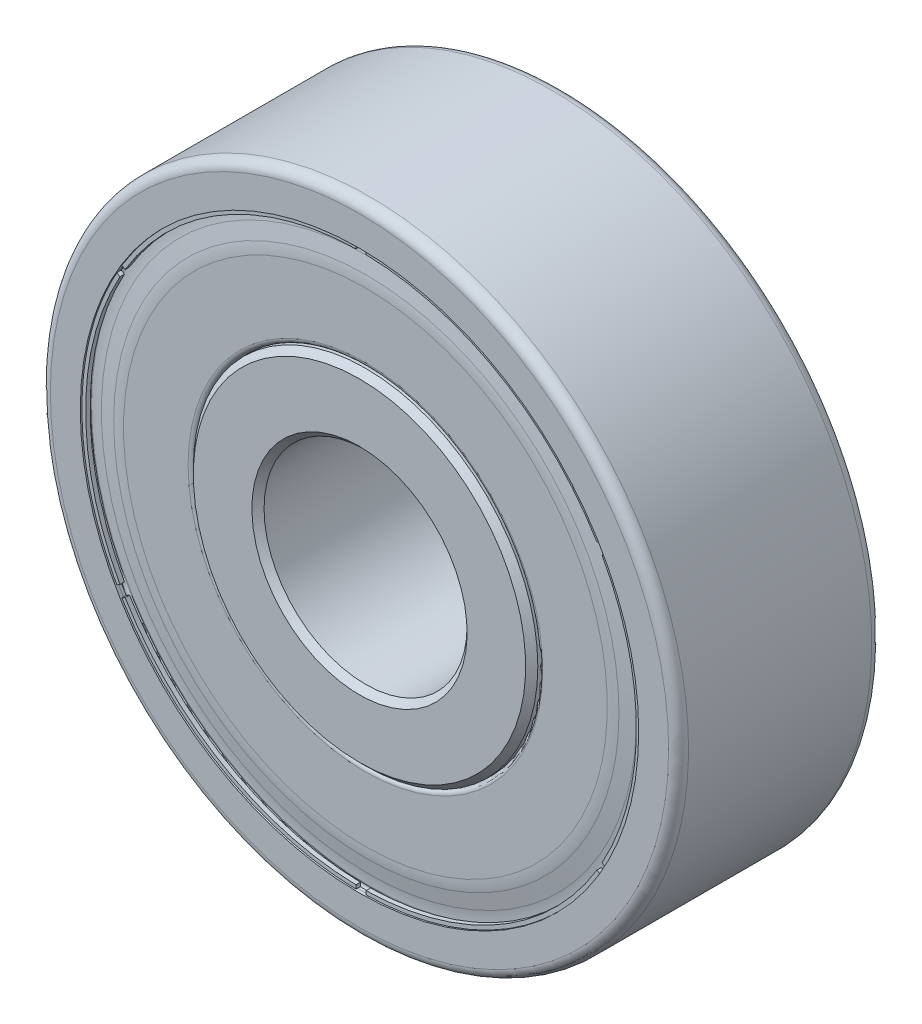
SolidWorks part; units mm, degrees
ref_plane "Front Plane" through (0, 0, 0) normal (0, 0, 1) x (1, 0, 0)
ref_plane "Top Plane" through (0, 0, 0) normal (0, 1, 0) x (1, 0, 0)
ref_plane "Right Plane" through (0, 0, 0) normal (1, 0, 0) x (0, 0, -1)
sketch "Sketch1" plane through (0, 0, 0) normal (0, 0, 1) x (1, 0, 0)
  line L0 (-11, 0) -> (-3.5, 0) construction
  line L1 (-3.5, 0) -> (3.5, 0) construction
  line L2 (3.5, 0) -> (11, 0) construction
  line L3 (0, 11) -> (0, 3.5) construction
  line L4 (0, 3.5) -> (0, 0) construction
  circle A0 centre (0, 0) radius 3.5 construction
  circle A1 centre (0, 0) radius 11 construction
  point P0 (0, 0)
  point P9 (0, 11)
  point P10 (0, 3.5)
  dimension "For Housing ID" = 22
  dimension "For Shaft Diameter" = 7
  dimension "OD" = 22
  dimension "ID" = 7
sketch "Sketch2" plane through (0, 0, 0) normal (1, 0, 0) x (0, 0, -1)
  line L1 (-3.5, -11) -> (3.5, -11) construction
  line L2 (-3.5, -11) -> (-3.5, 11) construction
  line L3 (-3.5, 11) -> (3.5, 11) construction
  line L4 (3.5, -11) -> (3.5, 11) construction
  line L5 (0, 11) -> (0, -11) construction
  line L6 (-3.5, 0) -> (3.5, 0) construction
  dimension "Width" = 7
sketch "Sketch3" plane through (0, 0, 0) normal (1, 0, 0) x (0, 0, -1)
  line L0 (-3.1562, 11) -> (3.5, 11) construction
  line L1 (-3.5, 3.5) -> (3.5, 3.5)
  line L2 (-3.5, -11) -> (-3.5, 11) construction
  line L3 (3.5, -11) -> (3.5, 11) construction
  line L4 (-3.5, 3.5) -> (-3.5, 5.9375)
  line L5 (-3.5, 5.9375) -> (3.5, 5.9375) construction
  line L6 (3.5, 5.9375) -> (3.5, 3.5)
  line L7 (-3.5, 11) -> (-3.5, 9.625) construction
  line L8 (-3.5, 9.625) -> (3.5, 9.625) construction
  line L9 (3.5, 9.625) -> (3.5, 11) construction
  line L10 (0, 9.625) -> (0, 5.9375) construction
  line L11 (0, 9.9687) -> (0, 9.625) construction
  line L12 (0, 9.9687) -> (0, 10.3125) construction
  line L13 (0, 11) -> (0, 3.5) construction
  line L14 (0, 10.3125) -> (0, 10.6562) construction
  line L15 (0, 10.6562) -> (0, 11) construction
  line L21 (3.5, 9.625) -> (3.395, 9.625)
  line L22 (-3.5, 9.625) -> (-3.395, 9.625)
  line L23 (-3.0477, 9.6554) -> (-2.9453, 9.075)
  line L24 (-2.9453, 9.075) -> (-1.7639, 9.075)
  line L25 (1.7639, 9.075) -> (2.9453, 9.075)
  line L26 (2.9453, 9.075) -> (3.0477, 9.6554)
  line L27 (-3.5, 5.9375) -> (-1.1772, 5.9375)
  line L28 (3.5, 5.9375) -> (1.1772, 5.9375)
  line L29 (-3.1562, 11) -> (3.1562, 11)
  line L31 (3.5, 10.6563) -> (3.5, 9.625)
  line L33 (-3.5, 10.6563) -> (-3.5, 9.625)
  circle A0 centre (0, 7.7812) radius 2.1875 construction
  arc A3 (-3.395, 9.625) -> (-3.0477, 9.6554) centre (-3.22, 9.625) cw
  arc A4 (3.0477, 9.6554) -> (3.395, 9.625) centre (3.22, 9.625) cw
  arc A5 (-1.7639, 9.075) -> (1.7639, 9.075) centre (0, 7.7812) cw
  arc A8 (-1.1772, 5.9375) -> (1.1772, 5.9375) centre (0, 7.7812) ccw
  arc A9 (-3.1562, 11) -> (-3.5, 10.6563) centre (-3.1562, 10.6562) ccw
  arc A10 (3.5, 10.6563) -> (3.1562, 11) centre (3.1562, 10.6562) ccw
  dimension "D1" = 4.375
  dimension "D5" = 0.175
  dimension "REF" = 7.5
  dimension "D2" = 1.375
  dimension "D3" = 0.105
  dimension "D4" = 10
  dimension "D6" = 0.55
revolve "Revolve1" add sketch "Sketch3" angle 360 about L6
sketch "Sketch7" plane through (0, 0, 0) normal (0, 0, 1) x (1, 0, 0)
  line L0 (0, 11) -> (0, 0) construction
  line L1 (0, 5.5937) -> (0, 9.9687) construction
  line L2 (-2.0993, 7.1663) -> (0, 0) construction
  line L3 (0, 0) -> (2.0993, 7.1663) construction
  circle A0 centre (0, 7.7812) radius 2.1875 construction
  point P8 (0, 5.5937)
  dimension "Bearing Spacing" = 32.655
chamfer "Chamfer1" distance 0.21 angle 45 4 edges at (0, -3.5, -3.5) (0, -5.9375, -3.5) (0, -3.5, 3.5) (0, -5.9375, 3.5)
sketch "Sketch4" plane through (0, 0, 0) normal (1, 0, 0) x (0, 0, -1)
  line L0 (-3.395, 9.625) -> (-3.4475, 9.625)
  line L1 (-3.4475, 9.625) -> (-3.4475, 9.493)
  line L2 (-2.9453, 9.075) -> (-3.0477, 9.6554) construction
  line L3 (-3.4475, 9.625) -> (-3.5, 9.625) construction
  line L4 (-3.045, 9.625) -> (-3.045, 9.405)
  line L19 (-3.145, 9.405) -> (-3.045, 9.405) construction
  line L23 (-3.195, 8.525) -> (-3.195, 6.0375) construction
  line L25 (-3.195, 6.0375) -> (-2.1283, 6.0375) construction
  line L26 (-2.1283, 6.0375) -> (-2.1283, 5.9375)
  line L28 (-2.1283, 5.9375) -> (-3.295, 5.9375) construction
  line L29 (-3.295, 5.9375) -> (-3.295, 8.525) construction
  line L30 (-3.045, 9.405) -> (-3.195, 8.525)
  line L31 (-3.145, 9.405) -> (-3.145, 9.625)
  line L33 (-3.5, 5.9375) -> (-1.1772, 5.9375) construction
  line L35 (-3.4475, 9.493) -> (-3.295, 9.493)
  line L36 (-3.295, 9.493) -> (-3.295, 9.625)
  line L37 (-3.195, 7.2812) -> (-3.295, 7.2813) construction
  line L38 (-3.145, 9.405) -> (-3.295, 8.525)
  line L39 (-3.295, 9.493) -> (-3.295, 8.525) construction
  line L41 (-3.12, 5.9375) -> (-2.1283, 5.9375)
  line L42 (-3.12, 6.0375) -> (-2.1283, 6.0375)
  line L43 (-3.195, 6.1125) -> (-3.195, 8.525)
  line L44 (-3.295, 8.525) -> (-3.295, 6.1125)
  arc A0 (-3.045, 9.625) -> (-3.395, 9.625) centre (-3.22, 9.625) ccw
  arc A8 (-3.0477, 9.6554) -> (-3.395, 9.625) centre (-3.22, 9.625) ccw construction
  arc A9 (-3.145, 9.625) -> (-3.295, 9.625) centre (-3.22, 9.625) ccw
  arc A10 (-3.295, 6.1125) -> (-3.12, 5.9375) centre (-3.12, 6.1125) ccw
  arc A11 (-3.195, 6.1125) -> (-3.12, 6.0375) centre (-3.12, 6.1125) ccw
  point P24 (-3.0035, 9.405)
  dimension "D4" = 0.35
  dimension "D1" = 0.132
  dimension "D2" = 0.1
  dimension "D5" = 1.1667
  dimension "D6" = 0.22
  dimension "D3" = 0.88
revolve "Revolve2" add sketch "Sketch4" angle 360 about L6
fillet "Fillet1" radius 2.2 2 edges at (0, -8.525, 3.295) (0, -9.405, 3.145)
sketch "Sketch5" plane through (0, 0, 0) normal (1, 0, 0) x (0, 0, -1)
  line L0 (0, 9.9687) -> (0, 5.5937)
  circle A0 centre (0, 7.7812) radius 2.1875 construction
  arc A1 (0, 5.5937) -> (0, 9.9687) centre (0, 7.7812) ccw
revolve "Revolve3" add sketch "Sketch5" angle 360 about L0
pattern_circular "CirPattern1" count 6 over 360 about axis through (0, 0, 0) along (0, 0, 1) of bodies 107
sketch "Sketch6" plane through (0, 0, 3.4475) normal (0, 0, 1) x (1, 0, 0)
  line L0 (0, 9.625) -> (0, 0) construction
  line L1 (-0.175, 9.6234) -> (-0.175, 9.4914)
  line L2 (0.175, 9.6234) -> (0.175, 9.4914)
  line L3 (-0.175, 9.5574) -> (0.175, 9.5574) construction
  arc A0 (0.175, 9.4914) -> (-0.175, 9.4914) centre (0, 0) ccw
  arc A1 (0.175, 9.6234) -> (-0.175, 9.6234) centre (0, 0) ccw
  circle A7 centre (0, 0) radius 9.625 construction
  circle A8 centre (0, 0) radius 9.493 construction
  circle A9 centre (0, 0) radius 9.625 construction
  circle A10 centre (0, 0) radius 9.493 construction
  point P13 (0, 9.5574)
  dimension "D1" = 0.35
extrude "Cut-Extrude1" cut sketch "Sketch6" against normal up to surface (0.1525 mm away) up to face at (0, -9.625, 3.295)
pattern_circular "CirPattern2" count 6 over 360 about axis through (0, 0, 0) along (0, 0, 1) of "Cut-Extrude1"
mirror "Mirror2" about plane through (0, 0, 0) normal (0, 0, 1) of bodies 127 106
equation "\"D1@Sketch3\"=\"Width@Sketch2\"*.625"
equation "\"D2@Sketch3\"=\"OD@Sketch1\" * .0625"
equation "\"D3@Sketch3\"=\"Width@Sketch2\"*.015"
equation "\"D5@Sketch3\"=\"Width@Sketch2\"*.025"
equation "\"D6@Sketch3\" = \"OD@Sketch1\" * .025"
equation "\"D1@Chamfer1\"=\"Width@Sketch2\"*.03"
equation "\"D1@Fillet1\"=\"OD@Sketch1\"*.1"
equation "\"D1@CirPattern1\"=(360/\"Bearing Spacing@Sketch7\")-5"
equation "\"D1@CirPattern2\" = ( 360 / \"Bearing Spacing@Sketch7\" ) - 5"
equation "\"D1@Sketch4\"=\"OD@Sketch1\" *.006"
equation "\"D5@Sketch4\"=\"Width@Sketch2\"/6"
equation "\"D6@Sketch4\"=\"OD@Sketch1\" * .01"
equation "\"D3@Sketch4\"=\"OD@Sketch1\" *.04"
equation "\"D1@Sketch6\"=\"Width@Sketch2\"*.05"
equation "\"D4@Sketch4\"=\"Width@Sketch2\"*.05"
